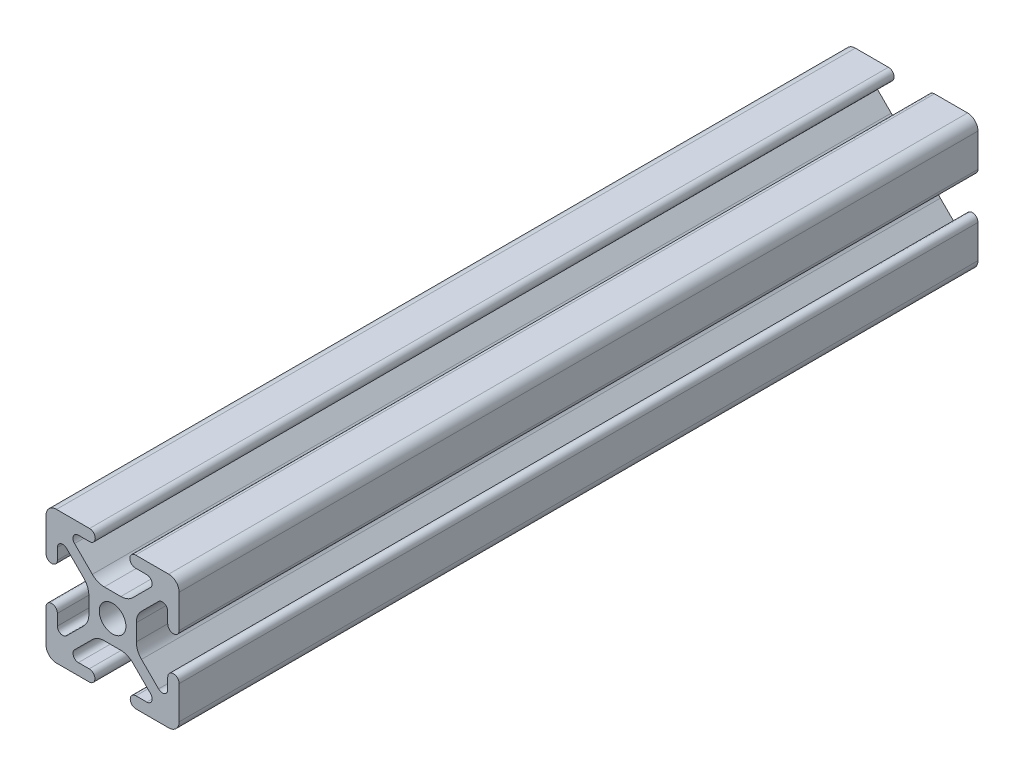
SolidWorks part; units mm, degrees
material "6005A-T61"
ref_plane "Front Plane" through (0, 0, 0) normal (0, 0, 1) x (1, 0, 0)
ref_plane "Top Plane" through (0, 0, 0) normal (0, 1, 0) x (1, 0, 0)
ref_plane "Right Plane" through (0, 0, 0) normal (1, 0, 0) x (0, 0, -1)
sketch "Sketch1" plane through (0, 0, 0) normal (0, 0, 1) x (1, 0, 0)
  line L0 (-8.6363, 7.1116) -> (-5.4322, 3.9121)
  line L1 (-4.455, 1.5554) -> (-4.455, -1.5554)
  line L2 (-5.4322, -3.9121) -> (-8.6363, -7.1116)
  line L3 (-10.36, -6.3969) -> (-10.36, -4.32)
  line L4 (-12.5, -4.32) -> (-12.5, -8.6518)
  line L5 (-12.5, -8.6518) -> (-12.5, -10.5371)
  line L6 (-10.5371, -12.5) -> (-8.4416, -12.5)
  line L7 (-8.4416, -12.5) -> (-4.3879, -12.5)
  line L8 (-4.3879, -10.36) -> (-6.42, -10.36)
  line L9 (-7.1337, -8.6353) -> (-3.7953, -5.3018)
  line L10 (-1.5554, -4.375) -> (1.5554, -4.375)
  line L11 (10.36, 4.32) -> (10.36, 6.3969)
  line L12 (12.5, 7.9913) -> (12.5, 4.32)
  line L13 (12.5, 10.5371) -> (12.5, 7.9913)
  line L14 (4.32, 12.5) -> (10.5371, 12.5)
  line L16 (6.42, 10.36) -> (4.32, 10.36)
  line L17 (3.7953, 5.3018) -> (7.1337, 8.6353)
  line L18 (7.1337, -8.6353) -> (3.7953, -5.3018)
  line L19 (4.3879, -10.36) -> (6.42, -10.36)
  line L20 (8.4416, -12.5) -> (4.3879, -12.5)
  line L21 (10.5371, -12.5) -> (8.4416, -12.5)
  line L22 (12.5, -8.6518) -> (12.5, -10.5371)
  line L23 (12.5, -4.32) -> (12.5, -8.6518)
  line L24 (10.36, -6.3969) -> (10.36, -4.32)
  line L25 (5.4322, -3.9121) -> (8.6363, -7.1116)
  line L26 (4.455, 1.5554) -> (4.455, -1.5554)
  line L27 (8.6363, 7.1116) -> (5.4322, 3.9121)
  line L28 (1.5554, 4.375) -> (-1.5554, 4.375)
  line L29 (-3.7953, 5.3018) -> (-7.1337, 8.6353)
  line L30 (-6.42, 10.36) -> (-4.32, 10.36)
  line L32 (-4.32, 12.5) -> (-10.5371, 12.5)
  line L33 (-12.5, 10.5371) -> (-12.5, 7.9913)
  line L34 (-12.5, 7.9913) -> (-12.5, 4.32)
  line L35 (-10.36, 4.32) -> (-10.36, 6.3969)
  line L36 (-15.7693, 0) -> (12.5, 0) construction
  line L37 (0, 13.9334) -> (0, -12.3541) construction
  circle A0 centre (0, 0) radius 2.5
  arc A1 (-8.6363, 7.1116) -> (-10.36, 6.3969) centre (-9.35, 6.3969) ccw
  arc A2 (-4.455, 1.5554) -> (-5.4322, 3.9121) centre (-7.7855, 1.5554) ccw
  arc A3 (-5.4322, -3.9121) -> (-4.455, -1.5554) centre (-7.7855, -1.5554) ccw
  arc A4 (-10.36, -6.3969) -> (-8.6363, -7.1116) centre (-9.35, -6.3969) ccw
  arc A5 (-10.36, -4.32) -> (-12.5, -4.32) centre (-11.43, -4.32) ccw
  arc A6 (-12.5, -10.5371) -> (-10.5371, -12.5) centre (-10.5371, -10.5371) ccw
  arc A7 (-4.3879, -12.5) -> (-4.3879, -10.36) centre (-4.3879, -11.43) ccw
  arc A8 (-7.1337, -8.6353) -> (-6.42, -10.36) centre (-6.42, -9.35) ccw
  arc A9 (-1.5554, -4.375) -> (-3.7953, -5.3018) centre (-1.5554, -7.545) ccw
  arc A10 (12.5, 4.32) -> (10.36, 4.32) centre (11.43, 4.32) cw
  arc A11 (10.5371, 12.5) -> (12.5, 10.5371) centre (10.5371, 10.5371) cw
  arc A12 (4.32, 10.36) -> (4.32, 12.5) centre (4.32, 11.43) cw
  arc A13 (6.42, 10.36) -> (7.1337, 8.6353) centre (6.42, 9.35) cw
  arc A14 (3.7953, 5.3018) -> (1.5554, 4.375) centre (1.5554, 7.545) cw
  arc A15 (1.5554, -4.375) -> (3.7953, -5.3018) centre (1.5554, -7.545) cw
  arc A16 (7.1337, -8.6353) -> (6.42, -10.36) centre (6.42, -9.35) cw
  arc A17 (4.3879, -12.5) -> (4.3879, -10.36) centre (4.3879, -11.43) cw
  arc A18 (12.5, -10.5371) -> (10.5371, -12.5) centre (10.5371, -10.5371) cw
  arc A19 (10.36, -4.32) -> (12.5, -4.32) centre (11.43, -4.32) cw
  arc A20 (10.36, -6.3969) -> (8.6363, -7.1116) centre (9.35, -6.3969) cw
  arc A21 (5.4322, -3.9121) -> (4.455, -1.5554) centre (7.7855, -1.5554) cw
  arc A22 (4.455, 1.5554) -> (5.4322, 3.9121) centre (7.7855, 1.5554) cw
  arc A23 (8.6363, 7.1116) -> (10.36, 6.3969) centre (9.35, 6.3969) cw
  arc A24 (-3.7953, 5.3018) -> (-1.5554, 4.375) centre (-1.5554, 7.545) ccw
  arc A25 (-6.42, 10.36) -> (-7.1337, 8.6353) centre (-6.42, 9.35) ccw
  arc A26 (-4.32, 10.36) -> (-4.32, 12.5) centre (-4.32, 11.43) ccw
  arc A27 (-10.5371, 12.5) -> (-12.5, 10.5371) centre (-10.5371, 10.5371) ccw
  arc A28 (-12.5, 4.32) -> (-10.36, 4.32) centre (-11.43, 4.32) ccw
  dimension "D4" = 14.86
  dimension "D5" = 2.14
  dimension "D6" = 6.5
  dimension "D7" = 8.75
  dimension "D8" = 1.01
  dimension "D9" = 3.17
  dimension "D14" = 5
  dimension "D1" = 25
  dimension "D2" = 8.91
  dimension "D3" = 12.5
  dimension "D12" = 2.14
extrude "Extrude1" add sketch "Sketch1" against normal blind 150
